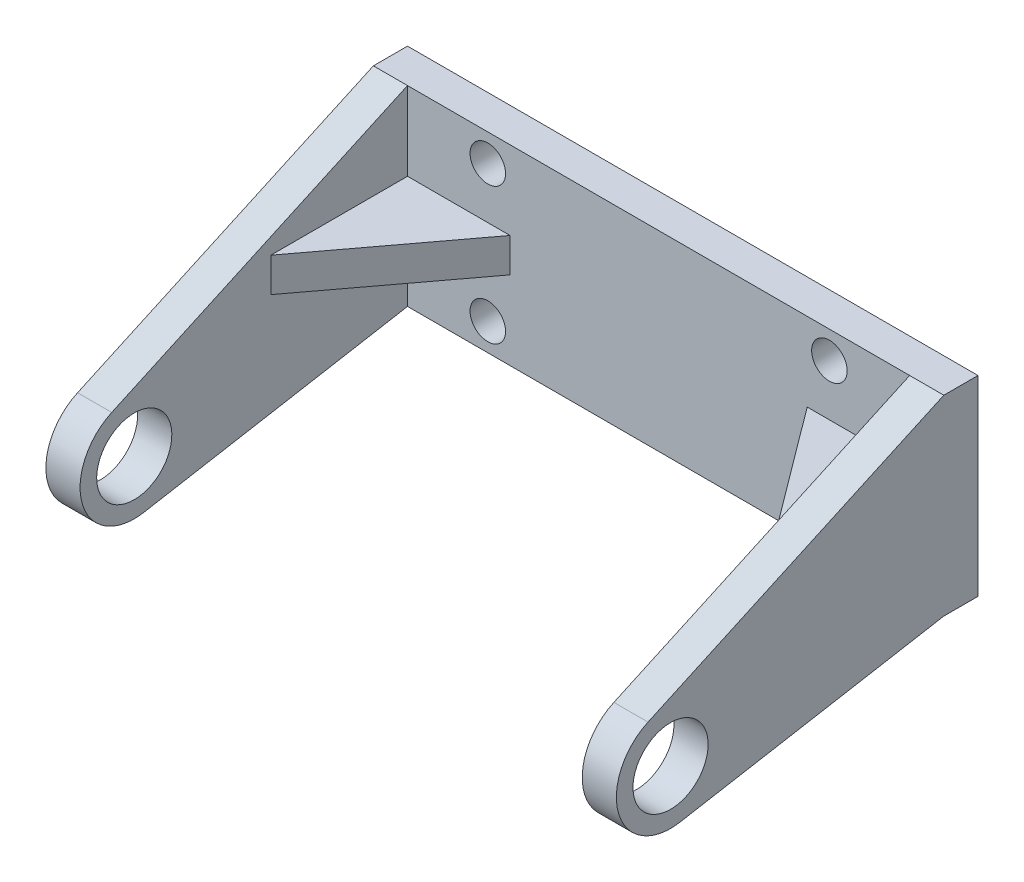
SolidWorks part; units mm, degrees
ref_plane "前视基准面" through (0, 0, 0) normal (0, 0, 1) x (1, 0, 0)
ref_plane "上视基准面" through (0, 0, 0) normal (0, 1, 0) x (1, 0, 0)
ref_plane "右视基准面" through (0, 0, 0) normal (1, 0, 0) x (0, 0, -1)
sketch "草图1" plane through (0, 0, 0) normal (0, 0, 1) x (1, 0, 0)
  line L1 (-41.75, 14) -> (41.75, 14)
  line L2 (-41.75, 14) -> (-41.75, -14)
  line L3 (-41.75, -14) -> (41.75, -14)
  line L4 (41.75, 14) -> (41.75, -14)
  line L5 (-41.75, 14) -> (41.75, -14) construction
  line L6 (-41.75, -14) -> (41.75, 14) construction
  point P0 (0, 0)
  dimension "D1" = 28
  dimension "D2" = 83.5
extrude "凸台-拉伸1" add sketch "草图1" along normal blind 5
sketch "草图2" plane through (-41.75, 0, 0) normal (-1, 0, 0) x (0, 0, 1)
  line L3 (5, 14) -> (5, -14)
  line L5 (5, -14) -> (43.6228, -20.8102)
  line L6 (5, 14) -> (48.2965, -5.7868)
  line L7 (5, 14) -> (0, 14) construction
  arc A0 (43.6228, -20.8102) -> (48.2965, -5.7868) centre (45, -13) ccw
  circle A1 centre (45, -13) radius 5.5
  dimension "D2" = 11
  dimension "D4" = 100
  dimension "D1" = 40
  dimension "D3" = 27
extrude "凸台-拉伸2" add sketch "草图2" against normal blind 5
sketch "草图3" plane through (41.75, 0, 0) normal (1, 0, 0) x (0, 0, -1)
  line L3 (-5, 14) -> (-48.2965, -5.7868)
  line L4 (-43.6228, -20.8102) -> (-5, -14)
  line L5 (-5, -14) -> (-5, 14)
  line L6 (-5, 14) -> (-48.2965, -5.7868)
  line L7 (-43.6228, -20.8102) -> (-5, -14)
  line L8 (-5, -14) -> (-5, 14)
  circle A0 centre (-45, -13) radius 5.5 construction
  arc A1 (-48.2965, -5.7868) -> (-43.6228, -20.8102) centre (-45, -13) ccw
  arc A2 (-48.2965, -5.7868) -> (-43.6228, -20.8102) centre (-45, -13) ccw
  circle A3 centre (-45, -13) radius 5.5
  dimension "D1" = 0
extrude "凸台-拉伸3" add sketch "草图3" against normal blind 5
sketch "草图4" plane through (0, 0, 5) normal (0, 0, 1) x (1, 0, 0)
  line L1 (25, 10) -> (-25, 10) construction
  line L2 (25, 10) -> (25, -10) construction
  line L3 (25, -10) -> (-25, -10) construction
  line L4 (-25, 10) -> (-25, -10) construction
  line L5 (25, 10) -> (-25, -10) construction
  line L6 (25, -10) -> (-25, 10) construction
  circle A0 centre (-25, 10) radius 2.6
  circle A1 centre (25, 10) radius 2.6
  circle A2 centre (25, -10) radius 2.6
  circle A3 centre (-25, -10) radius 2.6
  point P0 (0, 0)
  dimension "D3" = 5.2
  dimension "D1" = 50
  dimension "D2" = 20
extrude "切除-拉伸2" cut sketch "草图4" against normal blind 5
sketch "草图5" plane through (0, 0, 0) normal (0, 1, 0) x (1, 0, 0)
  line L0 (-36.75, -5) -> (-21.75, -5)
  line L1 (36.75, -5) -> (-36.75, -5) construction
  line L2 (-21.75, -5) -> (-36.75, -25)
  line L3 (-36.75, -48.2965) -> (-36.75, -5) construction
  line L4 (-36.75, -25) -> (-36.75, -5)
  line L5 (36.75, -5) -> (36.75, -25.0855)
  line L6 (36.75, -5) -> (36.75, -48.2965) construction
  line L7 (36.75, -25.0855) -> (21.75, -5)
  line L8 (21.75, -5) -> (36.75, -5)
  dimension "D1" = 15
  dimension "D2" = 20
extrude "凸台-拉伸4" add sketch "草图5" along normal mid plane 5
